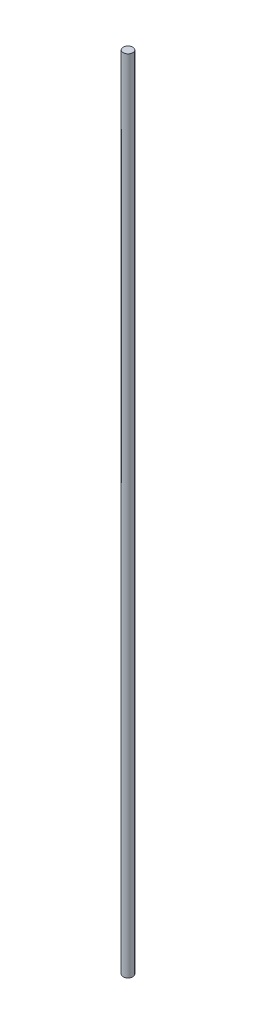
SolidWorks part; units mm, degrees
ref_plane "Front Plane" through (0, 0, 0) normal (0, 0, 1) x (1, 0, 0)
ref_plane "Top Plane" through (0, 0, 0) normal (0, 1, 0) x (1, 0, 0)
ref_plane "Right Plane" through (0, 0, 0) normal (1, 0, 0) x (0, 0, -1)
sketch "Sketch2" plane through (0, 0, 0) normal (0, 1, 0) x (1, 0, 0)
  circle A0 centre (0, 2.9868) radius 12.5
  dimension "D1" = 25
extrude "Boss-Extrude1" add sketch "Sketch2" along normal blind 2080
